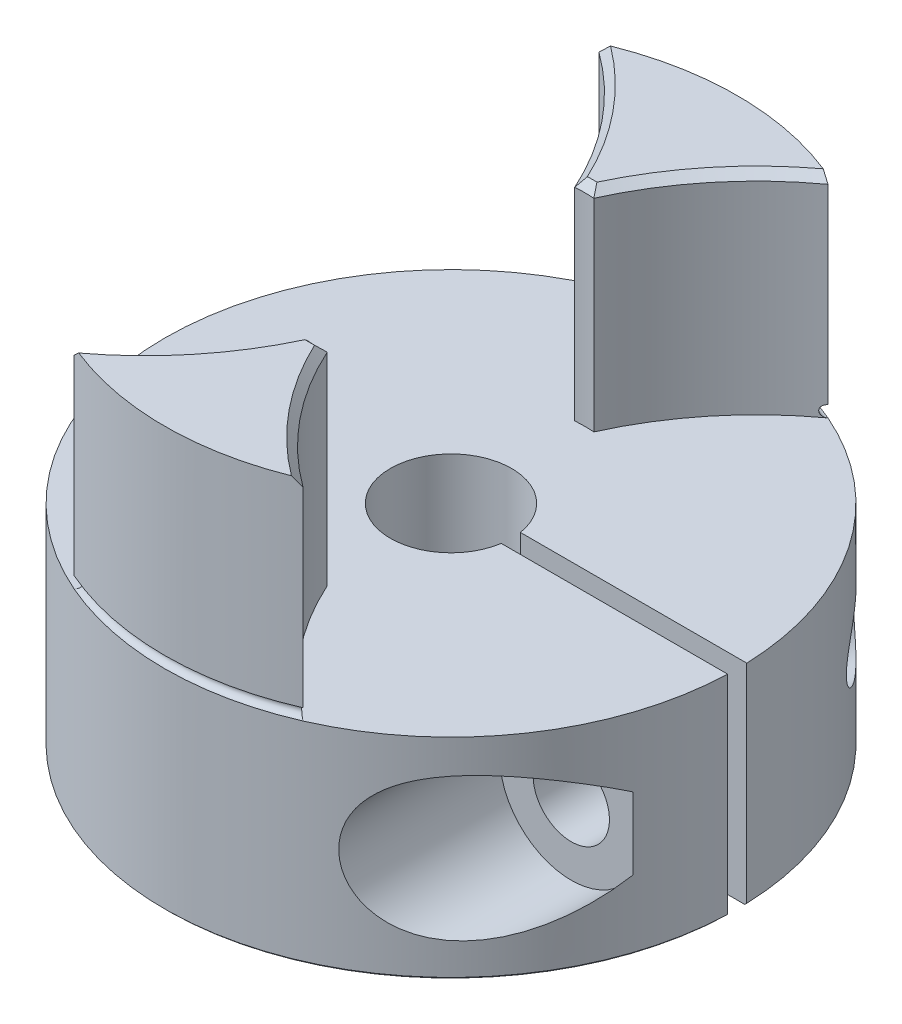
SolidWorks part; units mm, degrees
material "1060 Alloy"
ref_plane "Front" through (0, 0, 0) normal (0, 0, 1) x (1, 0, 0)
ref_plane "Top" through (0, 0, 0) normal (0, 1, 0) x (1, 0, 0)
ref_plane "Right" through (0, 0, 0) normal (1, 0, 0) x (0, 0, -1)
sketch "Sketch1" plane through (0, 0, 0) normal (0, 1, 0) x (1, 0, 0)
  circle A0 centre (0, 0) radius 15
extrude "Boss-Extrude1" add sketch "Sketch1" along normal mid plane 22
sketch "Sketch2" plane through (0, 11, 0) normal (0, 1, 0) x (1, 0, 0)
  circle A0 centre (0, 0) radius 7
  dimension "D1" = 14
extrude "Cut-Extrude1" cut sketch "Sketch2" against normal blind 23
sketch "Sketch3" plane through (0, 11, 0) normal (0, 1, 0) x (1, 0, 0)
  line L0 (-19.0209, 0) -> (26.8019, 0) construction
  line L1 (0, 17.1133) -> (0, -22.8638) construction
  line L2 (6, 13.7477) -> (6, 19.4636) construction
  circle A0 centre (16, 0) radius 17
  circle A1 centre (0, 0) radius 15 construction
  circle A2 centre (0, 0) radius 15 construction
  dimension "D2" = 34
  dimension "D1" = 6
extrude "Cut-Extrude2" cut sketch "Sketch3" against normal blind 11
sketch "Sketch4" plane through (0, 11, 0) normal (0, 1, 0) x (1, 0, 0)
  line L0 (0, 15) -> (0, -15) construction
  line L1 (-15, 0) -> (15, 0) construction
  arc A0 (6, 13.7477) -> (6, -13.7477) centre (0, 0) ccw construction
  arc A1 (6, -13.7477) -> (6, 13.7477) centre (0, 0) ccw construction
  arc A4 (0.5, -6.9821) -> (6, -13.7477) centre (16, 0) ccw construction
  arc A6 (0.5, 6.9821) -> (0.5, -6.9821) centre (0, 0) ccw construction
  arc A8 (-6, 13.7477) -> (-6, -13.7477) centre (0, 0) ccw
  arc A9 (-0.5, -6.9821) -> (-6, -13.7477) centre (-16, 0) cw
  arc A10 (-6, 13.7477) -> (-0.5, 6.9821) centre (-16, 0) cw
  arc A11 (-0.5, 6.9821) -> (-0.5, -6.9821) centre (0, 0) ccw
extrude "Cut-Extrude3" cut sketch "Sketch4" against normal blind 11
sketch "Sketch5" plane through (0, 0, 0) normal (0, 1, 0) x (1, 0, 0)
  line L0 (0, 0) -> (23.6149, 0) construction
  line L2 (3.7246, 0.5) -> (19.8903, 0.5)
  line L3 (3.7246, 0.5) -> (3.7246, -0.5)
  line L4 (3.7246, -0.5) -> (19.8903, -0.5)
  line L5 (19.8903, 0.5) -> (19.8903, -0.5)
  line L6 (3.7246, 0.5) -> (19.8903, -0.5) construction
  line L7 (3.7246, -0.5) -> (19.8903, 0.5) construction
  point P3 (11.8074, 0)
  dimension "D1" = 1
extrude "Cut-Extrude4" cut sketch "Sketch5" against normal blind 21
sketch "Sketch6" plane through (0, 0, 0) normal (0, 0, 1) x (1, 0, 0)
  line L0 (0, 17.6778) -> (0, -16.8659) construction
  line L1 (-15, -5.5) -> (14.9917, -5.5) construction
  line L2 (-15, 0) -> (-15, -11) construction
  line L3 (14.9917, -11) -> (14.9917, 0) construction
  circle A0 centre (11, -5.5) radius 2
  dimension "D1" = 11
  dimension "D2" = 4
extrude "Cut-Extrude5" cut sketch "Sketch6" along normal blind 21
sketch "Sketch7" plane through (0, 0, 0.5) normal (0, 0, -1) x (-1, 0, 0)
  circle A0 centre (-11, -5.5) radius 3.75
extrude "Cut-Extrude6" cut sketch "Sketch7" against normal blind 21 from offset 4.2 offset against normal yes
hole_wizard "M4 Tapped Hole1" positions "Sketch8" profile "Sketch9" tap size "M4" standard "ISO"
sketch "Sketch8" plane through (0, 0, -0.5) normal (0, 0, 1) x (1, 0, 0)
  point P0 (11, -5.5)
sketch "Sketch9" plane through (11, -5.5, -0.5) normal (1, 0, 0) x (0, -1, 0)
  line L0 (0, 0) -> (0, 21.0914)
  line L1 (0, 21.0914) -> (1.65, 20.1)
  line L2 (1.65, 20.1) -> (1.65, 0)
  line L5 (1.65, 0) -> (0, 0)
  line L10 (0, 21.0914) -> (-1.65, 20.1) construction
  line L11 (0, -6.35) -> (0, 107.95) construction
  dimension "Tap Drill Dia." = 3.3
  dimension "Tap Drill Depth" = 20.1
  dimension "Drill Angle" = 118
cosmetic thread "Hole Thread1" parameters "D1"=11.2293, "D2"=4
chamfer "Chamfer1" distance 0.4 angle 45 6 edges at (2.8089, 11, 10.7235) (2.8089, 11, -10.7235) (-2.8089, 11, 10.7235) (-2.8089, 11, -10.7235) (0, 11, 7) (0, 11, -7)
sketch "Sketch10" plane through (0, 0, 0) normal (1, 0, 0) x (0, 0, -1)
  line L0 (0.5, 0) -> (17.5553, 0) construction
  line L1 (15, -11) -> (15, 11) construction
  line L2 (0, 3.3604) -> (0, -12.7174) construction
  circle A0 centre (15, 0.3) radius 0.3
  dimension "D1" = 0.6
revolve "Cut-Revolve1" cut sketch "Sketch10" angle 360 about L2
chamfer "Chamfer2" distance 0.1 angle 45 1 edges at (-15, -11, 0)
sketch "Çizim1" plane through (0, 0, 0) normal (0, 1, 0) x (1, 0, 0)
  line L0 (6.9821, 0.5) -> (3.1354, 0.5)
  line L1 (6.9821, -0.5) -> (3.1354, -0.5)
  arc A3 (3.1354, 0.5) -> (3.1354, -0.5) centre (0, 0) ccw
  arc A4 (6.9821, 0.5) -> (6.9821, -0.5) centre (0, 0) ccw
  dimension "D1" = 6.35
extrude "Yükseklik-Ekstrüzyon1" add sketch "Çizim1" against normal up to surface (11 mm away) up to face at (-0.0066, -11, 0)
